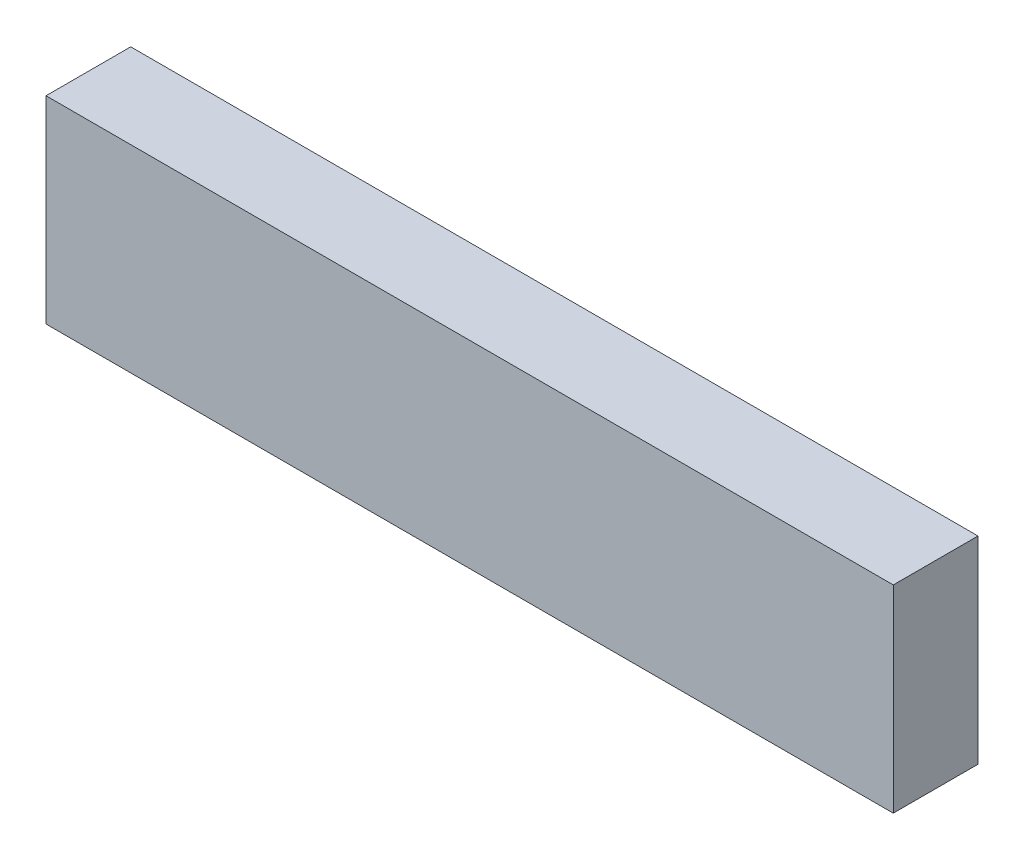
SolidWorks part; units mm, degrees
ref_plane "前视基准面" through (0, 0, 0) normal (0, 0, 1) x (1, 0, 0)
ref_plane "上视基准面" through (0, 0, 0) normal (0, 1, 0) x (1, 0, 0)
ref_plane "右视基准面" through (0, 0, 0) normal (1, 0, 0) x (0, 0, -1)
other "Configuration Table"
sketch "草图1" plane through (0, 0, 0) normal (0, 0, 1) x (1, 0, 0)
  line L1 (-150, -35) -> (150, -35)
  line L2 (-150, -35) -> (-150, 35)
  line L3 (-150, 35) -> (150, 35)
  line L4 (150, -35) -> (150, 35)
  line L5 (-150, -35) -> (150, 35) construction
  line L6 (-150, 35) -> (150, -35) construction
  point P0 (0, 0)
extrude "凸台-拉伸1" add sketch "草图1" along normal blind 30
